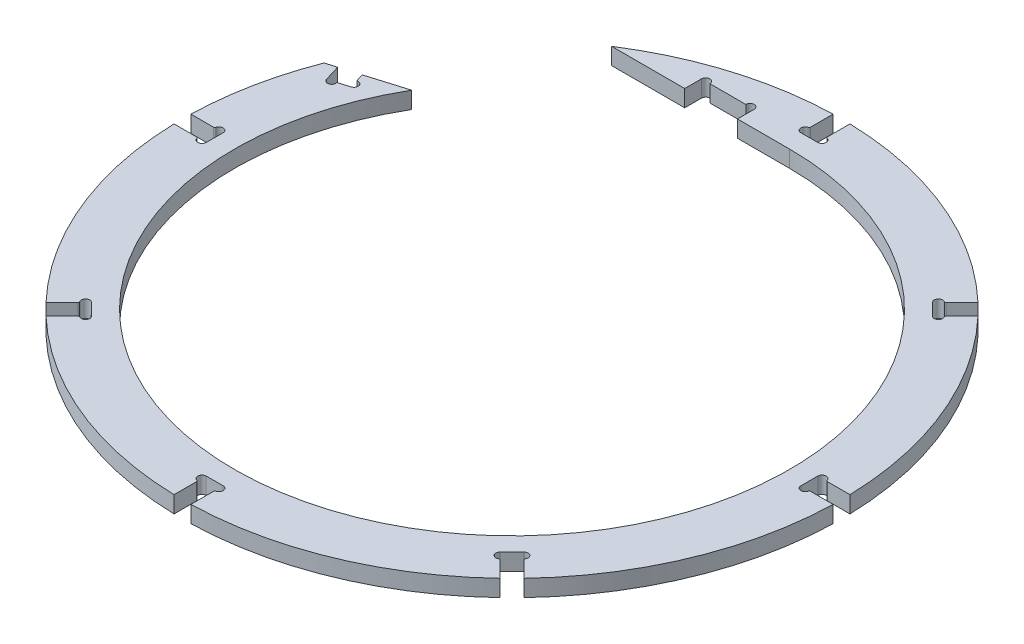
SolidWorks part; units mm, degrees
ref_plane "Front Plane" through (0, 0, 0) normal (0, 0, 1) x (1, 0, 0)
ref_plane "Top Plane" through (0, 0, 0) normal (0, 1, 0) x (1, 0, 0)
ref_plane "Right Plane" through (0, 0, 0) normal (1, 0, 0) x (0, 0, -1)
sketch "Sketch1" plane through (0, 0, 0) normal (0, 1, 0) x (1, 0, 0)
  circle A0 centre (0, 0) radius 210.5
  circle A1 centre (0, 0) radius 250
  dimension "D1" = 421
  dimension "D2" = 500
extrude "Boss-Extrude1" add sketch "Sketch1" along normal blind 12.7
sketch "Sketch2" plane through (0, 12.7, 0) normal (0, 1, 0) x (1, 0, 0)
  line L0 (0, 0) -> (0, 210.5) construction
  line L1 (0, 210.5) -> (0, 250) construction
  line L2 (0, 210.5) -> (0, 225.5) construction
  line L3 (0, 225.5) -> (0, 250) construction
  line L4 (6.4, 225.5) -> (6.4, 250) construction
  line L5 (-6.4, 225.5) -> (-6.4, 250) construction
  line L6 (6.4, 225.5) -> (-6.4, 225.5)
  line L7 (6.4, 250) -> (-6.4, 250)
  line L8 (-6.4, 250) -> (-6.4, 231.9)
  line L9 (6.4, 250) -> (6.4, 231.9)
  circle A0 centre (0, 0) radius 210.5 construction
  circle A1 centre (0, 0) radius 250 construction
  arc A2 (-6.4, 231.9) -> (-6.4, 225.5) centre (-6.4, 228.7) ccw
  arc A3 (6.4, 225.5) -> (6.4, 231.9) centre (6.4, 228.7) ccw
  dimension "D4" = 6.4
  dimension "D1" = 225.5
  dimension "D2" = 6.4
  dimension "D3" = 6.4
extrude "Cut-Extrude1" cut sketch "Sketch2" against normal through all
fillet "Fillet1" radius 1 2 edges at (6.4, 6.35, -231.9) (-6.4, 6.35, -231.9)
pattern_circular "CirPattern1" count 8 over 360 about axis through (0, 0, 0) along (0, 1, 0) of "Fillet1", "Cut-Extrude1"
sketch "Sketch5" plane through (0, 12.7, 0) normal (0, 1, 0) x (1, 0, 0)
  line L0 (0, 210.5) -> (-248.0445, 210.5)
  line L1 (-248.0445, 210.5) -> (-248.0445, 90.5)
  line L2 (-248.0445, 90.5) -> (-233.0445, 90.5)
  line L3 (0, 210.5) -> (0, 160.5)
  line L4 (0, 160.5) -> (-233.0445, 90.5)
  circle A0 centre (0, 0) radius 210.5 construction
  arc A1 (-181.2442, 172.1933) -> (-249.9181, 6.4) centre (0, 0) ccw construction
  dimension "D1" = 15
  dimension "D2" = 120
  dimension "D3" = 50
extrude "Cut-Extrude3" cut sketch "Sketch5" against normal through all
sketch "Sketch6" plane through (0, 12.7, 0) normal (0, 1, 0) x (1, 0, 0)
  line L0 (-6.4, 232.7792) -> (-6.4, 210.5) construction
  line L1 (0, 210.5) -> (-134.8694, 210.5) construction
  line L2 (-112.6133, 210.5) -> (-112.6133, 223.2) construction
  line L3 (-112.6133, 223.2) -> (-6.4, 223.2) construction
  line L4 (-112.6133, 210.5) -> (-6.4, 210.5) construction
  line L5 (-59.5067, 210.5) -> (-59.5067, 223.2) construction
  line L6 (-39.5067, 210.5) -> (-39.5067, 223.2)
  line L7 (-79.5067, 210.5) -> (-79.5067, 223.2)
  line L8 (-39.5067, 210.5) -> (-79.5067, 210.5)
  line L9 (-39.5067, 223.2) -> (-79.5067, 223.2) construction
  line L10 (-73.1067, 223.2) -> (-45.9067, 223.2)
  line L11 (-193.8983, 102.2584) -> (-241.9269, 87.832) construction
  line L12 (-233.0445, 90.5) -> (-181.9526, 105.8466) construction
  line L13 (-193.8983, 102.2584) -> (-190.2448, 90.0953) construction
  line L14 (-190.2448, 90.0953) -> (-238.2734, 75.6688) construction
  line L15 (-238.2734, 75.6688) -> (-241.9269, 87.832) construction
  line L16 (-217.9126, 95.0452) -> (-214.2591, 82.8821) construction
  line L17 (-225.0956, 92.8876) -> (-221.4421, 80.7245)
  line L18 (-210.7296, 97.2028) -> (-207.0762, 85.0396) construction
  line L19 (-225.0956, 92.8876) -> (-210.7296, 97.2028)
  line L20 (-221.4421, 80.7245) -> (-207.0762, 85.0396) construction
  line L21 (-215.3126, 82.5656) -> (-207.0762, 85.0396)
  line L22 (-210.7296, 97.2028) -> (-208.9173, 91.1691)
  arc A0 (-6.4, 249.9181) -> (-134.8694, 210.5) centre (0, 0) ccw construction
  arc A1 (-73.1067, 223.2) -> (-79.5067, 223.2) centre (-76.3067, 223.2) ccw
  arc A2 (-39.5067, 223.2) -> (-45.9067, 223.2) centre (-42.7067, 223.2) ccw
  arc A3 (-181.9526, 105.8466) -> (0, 210.5) centre (0, 0) ccw construction
  arc A4 (-233.0445, 90.5) -> (-249.9181, 6.4) centre (0, 0) ccw construction
  arc A5 (-221.4421, 80.7245) -> (-215.3126, 82.5656) centre (-218.3774, 81.6451) ccw
  arc A6 (-207.0762, 85.0396) -> (-208.9173, 91.1691) centre (-207.9967, 88.1043) ccw
  dimension "D4" = 6.4
  dimension "D8" = 6.4
  dimension "D1" = 12.7
  dimension "D5" = 12.7
  dimension "D2" = 20
  dimension "D3" = 20
  dimension "D6" = 7.5
  dimension "D7" = 7.5
extrude "Cut-Extrude4" cut sketch "Sketch6" against normal through all
sketch "Sketch7" plane through (0, 12.7, 0) normal (0, 1, 0) x (1, 0, 0)
  line L0 (-6.4, 232.7792) -> (-6.4, 210.5) construction
  line L1 (0, 210.5) -> (-39.5067, 210.5) construction
  line L2 (-45.9067, 223.2) -> (-6.4, 223.2) construction
  line L3 (-6.4, 210.5) -> (-260.7445, 210.5)
  line L4 (-193.8983, 102.2584) -> (-260.7445, 82.1797)
  line L5 (-193.8983, 102.2584) -> (-190.2448, 90.0953)
  line L6 (-260.7445, 70.0166) -> (-260.7445, 223.2) construction
  line L7 (-260.7445, 68.9192) -> (-190.2448, 90.0953)
  line L8 (-248.0445, 223.2) -> (-248.0445, 70.0166) construction
  line L10 (-260.7445, 82.1797) -> (-257.0911, 70.0166)
  line L11 (-210.7296, 97.2028) -> (-181.9526, 105.8466) construction
  line L12 (-248.0445, 70.0166) -> (-260.7445, 70.0166) construction
  line L13 (-225.0956, 92.8876) -> (-221.4421, 80.7245)
  line L14 (-210.7296, 97.2028) -> (-207.0762, 85.0396)
  line L15 (-39.5067, 210.5) -> (-39.5067, 223.2)
  line L16 (-39.5067, 223.2) -> (-79.5067, 223.2)
  line L17 (-79.5067, 223.2) -> (-79.5067, 210.5)
  line L18 (-79.5067, 210.5) -> (-39.5067, 210.5)
  line L19 (-6.4, 210.5) -> (-6.4, 223.2)
  line L20 (-6.4, 223.2) -> (-260.7445, 223.2)
  line L21 (-260.7445, 223.2) -> (-260.7445, 210.5)
  line L22 (-248.0445, 223.2) -> (-260.7445, 223.2) construction
  line L23 (-248.0445, 85.9944) -> (-244.3911, 73.8313)
  line L24 (-134.8694, 210.5) -> (-134.8694, 223.2)
  line L25 (-238.2734, 75.6688) -> (-241.9269, 87.832)
  line L26 (-260.7445, 70.0166) -> (-260.7445, 56.7057)
  arc A0 (-181.9526, 105.8466) -> (0, 210.5) centre (0, 0) ccw construction
  arc A1 (-6.4, 249.9181) -> (-134.8694, 210.5) centre (0, 0) ccw construction
  arc A2 (-233.0445, 90.5) -> (-249.9181, 6.4) centre (0, 0) ccw construction
  dimension "D1" = 12.7
  dimension "D2" = 15
  dimension "D3" = 12.7
  dimension "D4" = 33.1067
  dimension "D5" = 40
  dimension "D6" = 254.3445
  dimension "D7" = 69.7967
  dimension "D8" = 17.5742
  dimension "D9" = 15
  dimension "D10" = 13.2605
  dimension "D11" = 128.4694
  dimension "D12" = 50.1485
